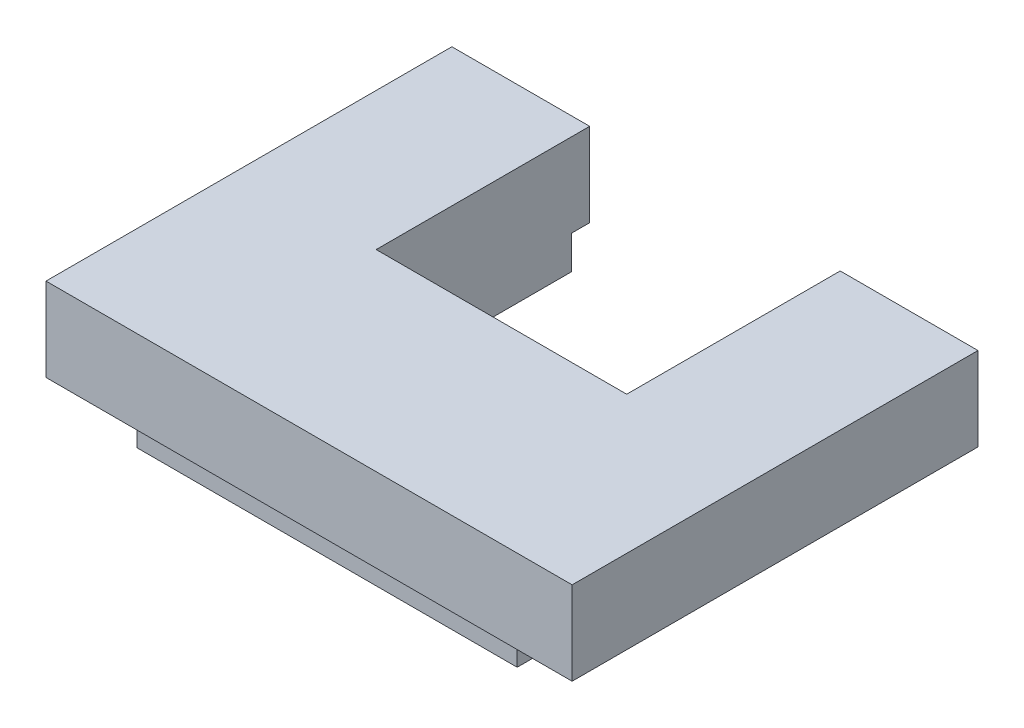
SolidWorks part; units mm, degrees
ref_plane "Front Plane" through (0, 0, 0) normal (0, 0, 1) x (1, 0, 0)
ref_plane "Top Plane" through (0, 0, 0) normal (0, 1, 0) x (1, 0, 0)
ref_plane "Right Plane" through (0, 0, 0) normal (1, 0, 0) x (0, 0, -1)
sketch "Sketch1" plane through (0, 0, 0) normal (0, 1, 0) x (1, 0, 0)
  line L1 (-400.05, -308.61) -> (400.05, -308.61)
  line L2 (-400.05, -308.61) -> (-400.05, 308.61)
  line L3 (-400.05, 308.61) -> (400.05, 308.61)
  line L4 (400.05, -308.61) -> (400.05, 308.61)
  line L5 (-400.05, -308.61) -> (400.05, 308.61) construction
  line L6 (-400.05, 308.61) -> (400.05, -308.61) construction
  point P0 (0, 0)
extrude "Boss-Extrude1" add sketch "Sketch1" against normal blind 304.8
sketch "Sketch3" plane through (0, -304.8, 0) normal (0, -1, 0) x (1, 0, 0)
  line L1 (-289.0496, -281.1802) -> (289.0496, -281.1802)
  line L2 (-289.0496, -281.1802) -> (-289.0496, 281.1802)
  line L3 (-289.0496, 281.1802) -> (289.0496, 281.1802)
  line L4 (289.0496, -281.1802) -> (289.0496, 281.1802)
  line L5 (-289.0496, -281.1802) -> (289.0496, 281.1802) construction
  line L6 (-289.0496, 281.1802) -> (289.0496, -281.1802) construction
  line L7 (-400.05, -308.61) -> (400.05, -308.61)
  line L8 (-400.05, -308.61) -> (-400.05, 308.61)
  line L9 (-400.05, 308.61) -> (400.05, 308.61)
  line L10 (400.05, -308.61) -> (400.05, 308.61)
  point P0 (0, 0)
extrude "Cut-Extrude1" cut sketch "Sketch3" against normal blind 177.8 from surface at 0 starting at face at (0, -304.8, 0)
sketch "Sketch5" plane through (0, 0, 281.1802) normal (0, 0, 1) x (1, 0, 0)
  line L0 (289.0496, -127) -> (289.0496, -304.8) construction
  line L1 (-289.0496, -304.8) -> (289.0496, -304.8)
  line L2 (-289.0496, -304.8) -> (-289.0496, -177.8)
  line L3 (-289.0496, -177.8) -> (289.0496, -177.8)
  line L4 (289.0496, -304.8) -> (289.0496, -177.8)
extrude "Cut-Extrude3" cut sketch "Sketch5" against normal through all
sketch "Sketch6" plane through (0, 0, 0) normal (0, 1, 0) x (1, 0, 0)
  line L0 (400.05, 308.61) -> (-400.05, 308.61) construction
  line L1 (190.5, -16.0561) -> (-190.5, -16.0561)
  line L2 (190.5, -16.0561) -> (190.5, 308.61)
  line L3 (190.5, 308.61) -> (-190.5, 308.61)
  line L4 (-190.5, -16.0561) -> (-190.5, 308.61)
  line L5 (190.5, -16.0561) -> (-190.5, 308.61) construction
  line L6 (190.5, 308.61) -> (-190.5, -16.0561) construction
  line L7 (0, -308.61) -> (0, 308.61) construction
  line L8 (-400.05, -308.61) -> (400.05, -308.61) construction
  point P0 (0, 146.2769)
extrude "Cut-Extrude4" cut sketch "Sketch6" against normal through all
